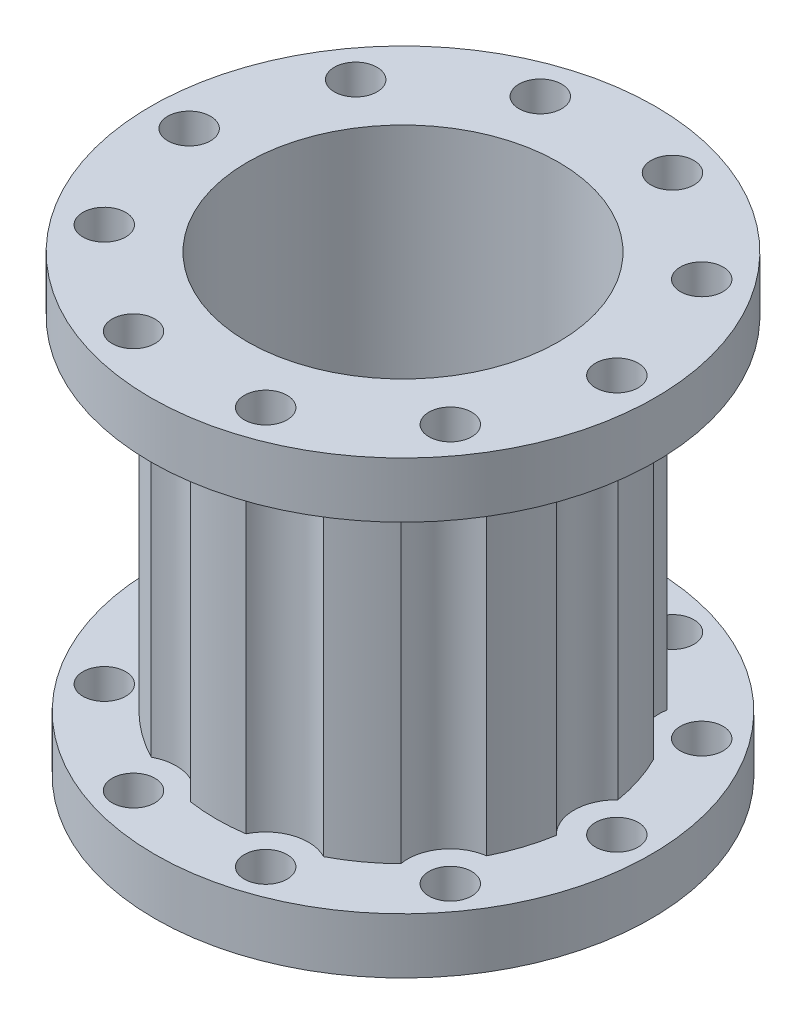
SolidWorks part; units mm, degrees
ref_plane "Front Plane" through (0, 0, 0) normal (0, 0, 1) x (1, 0, 0)
ref_plane "Top Plane" through (0, 0, 0) normal (0, 1, 0) x (1, 0, 0)
ref_plane "Right Plane" through (0, 0, 0) normal (1, 0, 0) x (0, 0, -1)
sketch "Sketch2" plane through (0, 0, 0) normal (0, 1, 0) x (1, 0, 0)
  circle A0 centre (0, 0) radius 21.825
  circle A1 centre (0, 0) radius 18.19
  dimension "D1" = 43.65
  dimension "D2" = 36.38
extrude "Boss-Extrude1" add sketch "Sketch2" along normal blind 40
sketch "Sketch3" plane through (0, 40, 0) normal (0, 1, 0) x (1, 0, 0)
  circle A0 centre (0, 0) radius 29.5
  dimension "D1" = 59
sketch "Sketch4" plane through (0, 40, 0) normal (0, 1, 0) x (1, 0, 0)
  circle A0 centre (0, 0) radius 29.5
  circle A1 centre (0, 0) radius 18.19 construction
  circle A2 centre (0, 0) radius 18.19
  dimension "D1" = 59
extrude "Boss-Extrude3" add sketch "Sketch4" along normal blind 6.5
sketch "Sketch5" plane through (0, 0, 0) normal (0, -1, 0) x (1, 0, 0)
  circle A0 centre (0, 0) radius 29
  circle A1 centre (0, 0) radius 18.19 construction
  circle A2 centre (0, 0) radius 18.19
  dimension "D1" = 58
extrude "Boss-Extrude4" add sketch "Sketch5" along normal blind 6.5
fillet "Fillet1" radius 2 1 edges at (0, 40, 21.825)
hole_wizard "Hole1" positions "Sketch6" profile "Sketch7" legacy end condition through all
sketch "Sketch6" plane through (0, -6.5, 0) normal (0, -1, 0) x (-1, 0, 0)
  point P0 (25, 0)
  dimension "D1" = 25
sketch "Sketch7" plane through (-25, -6.5, 0) normal (1, 0, 0) x (0, 0, -1)
  line L0 (0, 0) -> (0, 53)
  line L1 (0, 53) -> (2.5, 53)
  line L2 (2.5, 53) -> (2.5, 0)
  line L3 (2.5, 0) -> (0, 0)
  line L4 (0, 110) -> (0, -10) construction
  dimension "Diameter" = 5
  dimension "Depth" = 53
pattern_circular "CirPattern1" count 10 over 360 about axis through (0, 0, 0) along (0, 1, 0) of "Hole1"
sketch "Sketch9" plane through (0, 40, 0) normal (0, -1, 0) x (1, 0, 0)
  circle A0 centre (-20.2254, 14.6946) radius 5
  arc A1 (-20.4609, 12.2058) -> (-17.9311, 15.6877) centre (-20.2254, 14.6946) ccw construction
  dimension "D1" = 10
extrude "Cut-Extrude1" cut sketch "Sketch9" along normal up to surface (40 mm away) up to face at (-20.2254, 0, 12.1946)
pattern_circular "CirPattern2" count 10 over 360 about axis through (0, 0, 0) along (0, 1, 0) of "Cut-Extrude1"
